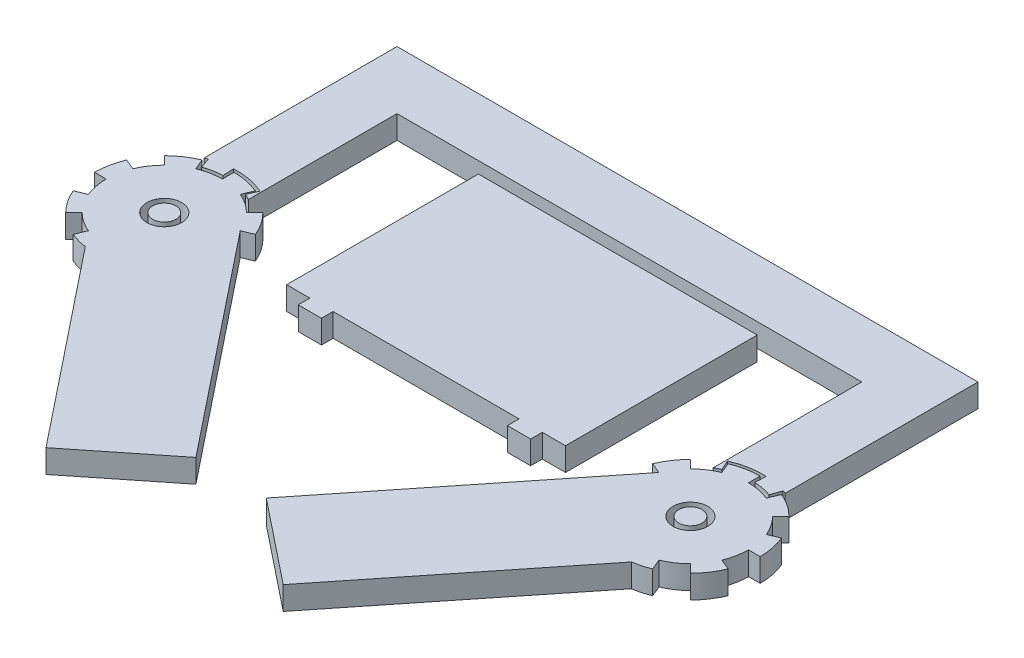
SolidWorks part; units mm, degrees
ref_plane "Front Plane" through (0, 0, 0) normal (0, 0, 1) x (1, 0, 0)
ref_plane "Top Plane" through (0, 0, 0) normal (0, 1, 0) x (1, 0, 0)
ref_plane "Right Plane" through (0, 0, 0) normal (1, 0, 0) x (0, 0, -1)
sketch "Sketch1" plane through (0, 0, 0) normal (0, 1, 0) x (1, 0, 0)
  line L0 (-20, 17.5) -> (20, 17.5)
  line L1 (-25, 22.5) -> (25, 22.5)
  line L2 (-25, 22.5) -> (-25, 5.8971)
  line L4 (25, 22.5) -> (25, 5.8971)
  line L5 (0, 0) -> (8.0037, 0)
  line L6 (0, 0) -> (-8.0037, 0)
  line L7 (20, 17.5) -> (20, 4.7044)
  line L9 (-20, 17.5) -> (-20, 4.7044)
  line L18 (0, 0) -> (0, -24.2528) construction
  line L19 (-23.5007, -5.8271) -> (-10.2099, -22.5)
  line L20 (-10.2099, -22.5) -> (-3.0312, -16.7775)
  line L21 (12, 0) -> (12, 16.5)
  line L22 (-12, 0) -> (-12, 16.5)
  line L23 (0, 17.5) -> (0, 16.5) construction
  line L24 (-12, 16.5) -> (12, 16.5)
  line L25 (-12, 0) -> (-10, 0) construction
  line L26 (-10, 0) -> (-10, -1)
  line L27 (-10, -1) -> (-8.0037, -1)
  line L28 (-8.0037, -1) -> (-8.0037, 0)
  line L29 (10, 0) -> (10, -1)
  line L30 (10, -1) -> (8.0037, -1)
  line L31 (8.0037, -1) -> (8.0037, 0)
  line L32 (-22.6382, 6.1106) -> (-22.6382, 5.1106)
  line L33 (-28.6382, 0.1106) -> (-27.6382, 0.1106)
  line L34 (-10, 0) -> (-12, 0)
  line L35 (10, 0) -> (12, 0)
  line L37 (-26.8808, -4.1321) -> (-26.1737, -3.4249)
  line L38 (-24.9343, -5.4327) -> (-24.5516, -4.5088)
  line L39 (-28.1814, -2.1855) -> (-27.2576, -1.8028)
  line L52 (-25, 22.5) -> (-25, -22.5) construction
  line L54 (-18.0188, 2.024) -> (-3.0312, -16.7775)
  line L55 (-20, 17.5) -> (-20, -17.5) construction
  line L58 (-20, -17.5) -> (20, -17.5) construction
  line L59 (-24.4164, 5.1054) -> (-24.7344, 5.9986)
  line L60 (-22.8806, 5.4069) -> (-22.9239, 6.3541)
  line L61 (-27.2576, 2.024) -> (-28.1814, 2.4067)
  line L62 (-20.5005, 4.9576) -> (-20.1161, 5.8291)
  line L63 (-26.1737, 3.6461) -> (-26.8808, 4.3532)
  line L64 (-24.5516, 4.73) -> (-24.9343, 5.6539)
  line L66 (-20.7247, 4.73) -> (-20.3421, 5.6539)
  line L67 (-19.1026, 3.6461) -> (-18.3955, 4.3532)
  line L68 (-18.0188, 2.024) -> (-17.0949, 2.4067)
  line L71 (10.2077, -22.5028) -> (3.0256, -16.7775)
  line L72 (23.5007, -5.8271) -> (10.2077, -22.5028)
  line L76 (25, 22.5) -> (25, 5.8971)
  line L77 (24.4164, 5.1054) -> (24.7344, 5.9986)
  line L78 (22.8806, 5.4069) -> (22.9239, 6.3541)
  line L79 (20.5005, 4.9576) -> (20.1161, 5.8291)
  line L80 (20, 17.5) -> (20, 4.7044)
  line L81 (18.0131, 2.024) -> (17.094, 2.4047)
  line L82 (19.1026, 3.6461) -> (18.3955, 4.3532)
  line L83 (20.7247, 4.73) -> (20.3421, 5.6539)
  line L84 (22.6382, 6.1106) -> (22.6382, 5.1106)
  line L85 (24.5516, 4.73) -> (24.9343, 5.6539)
  line L86 (26.1737, 3.6461) -> (26.8808, 4.3532)
  line L87 (27.2576, 2.024) -> (28.1814, 2.4067)
  line L88 (28.6382, 0.1106) -> (27.6382, 0.1106)
  line L89 (28.1814, -2.1855) -> (27.2576, -1.8028)
  line L90 (26.8808, -4.1321) -> (26.1737, -3.4249)
  line L91 (24.9343, -5.4327) -> (24.5516, -4.5088)
  line L98 (20, 17.5) -> (20, -17.5) construction
  line L100 (25, 22.5) -> (25, -22.5) construction
  line L101 (18.0131, 2.024) -> (3.0256, -16.7775)
  line L104 (-25, -22.5) -> (25, -22.5) construction
  arc A30 (-24.9343, 5.6539) -> (-26.8808, 4.3532) centre (-22.6382, 0.1106) ccw
  arc A31 (-26.1737, -3.4249) -> (-24.5516, -4.5088) centre (-22.6382, 0.1106) ccw
  arc A32 (-20.3421, 5.6539) -> (-22.6382, 6.1106) centre (-22.6382, 0.1106) ccw
  arc A33 (-17.0949, 2.4067) -> (-18.3955, 4.3532) centre (-22.6382, 0.1106) ccw
  arc A36 (-24.9343, -5.4327) -> (-23.5007, -5.8271) centre (-22.6382, 0.1106) ccw
  arc A37 (-28.1814, -2.1855) -> (-26.8808, -4.1321) centre (-22.6382, 0.1106) ccw
  arc A38 (-28.1814, 2.4067) -> (-28.6382, 0.1106) centre (-22.6382, 0.1106) ccw
  arc A39 (-25, 5.8971) -> (-24.7344, 5.9986) centre (-22.6382, 0.1106) cw
  arc A40 (-24.4164, 5.1054) -> (-22.8806, 5.4069) centre (-22.6382, 0.1106) cw
  arc A41 (-22.9239, 6.3541) -> (-20.1161, 5.8291) centre (-22.6382, 0.1106) cw
  arc A42 (-20, 4.7044) -> (-20.5005, 4.9576) centre (-22.6382, 0.1106) ccw
  arc A46 (-19.1026, 3.6461) -> (-20.7247, 4.73) centre (-22.6382, 0.1106) ccw
  arc A47 (-22.6382, 5.1106) -> (-24.5516, 4.73) centre (-22.6382, 0.1106) ccw
  arc A48 (-26.1737, 3.6461) -> (-27.2576, 2.024) centre (-22.6382, 0.1106) ccw
  arc A49 (-27.6382, 0.1106) -> (-27.2576, -1.8028) centre (-22.6382, 0.1106) ccw
  arc A50 (25, 5.8971) -> (24.7344, 5.9986) centre (22.6382, 0.1106) ccw
  arc A51 (24.4164, 5.1054) -> (22.8806, 5.4069) centre (22.6382, 0.1106) ccw
  arc A52 (22.9239, 6.3541) -> (20.1161, 5.8291) centre (22.6382, 0.1106) ccw
  arc A53 (20, 4.7044) -> (20.5005, 4.9576) centre (22.6382, 0.1106) cw
  arc A55 (17.094, 2.4047) -> (18.3955, 4.3532) centre (22.6382, 0.1106) cw
  arc A56 (19.1026, 3.6461) -> (20.7247, 4.73) centre (22.6382, 0.1106) cw
  arc A57 (20.3421, 5.6539) -> (22.6382, 6.1106) centre (22.6382, 0.1106) cw
  arc A58 (22.6382, 5.1106) -> (24.5516, 4.73) centre (22.6382, 0.1106) cw
  arc A59 (24.9343, 5.6539) -> (26.8808, 4.3532) centre (22.6382, 0.1106) cw
  arc A60 (26.1737, 3.6461) -> (27.2576, 2.024) centre (22.6382, 0.1106) cw
  arc A61 (28.1814, 2.4067) -> (28.6382, 0.1106) centre (22.6382, 0.1106) cw
  arc A62 (27.6382, 0.1106) -> (27.2576, -1.8028) centre (22.6382, 0.1106) cw
  arc A63 (28.1814, -2.1855) -> (26.8808, -4.1321) centre (22.6382, 0.1106) cw
  arc A64 (26.1737, -3.4249) -> (24.5516, -4.5088) centre (22.6382, 0.1106) cw
  arc A65 (24.9343, -5.4327) -> (23.5007, -5.8271) centre (22.6382, 0.1106) cw
  circle A70 centre (-22.6382, 0.1106) radius 1.004
  circle A71 centre (-22.6382, 0.1106) radius 1.498
  circle A72 centre (22.6382, 0.1106) radius 1.498
  circle A73 centre (22.6382, 0.1106) radius 1.004
  point P0 (0, 0)
  point P20 (0, 0)
  point P28 (0, 16.5)
  point P30 (-22.6382, 0.1106)
  point P34 (-22.6382, 0.1106)
  point P91 (-22.6382, 0.1106)
  point P98 (-22.6382, 0.1106)
  point P100 (-22.6382, 0.1106)
  dimension "D4" = 1
  dimension "D5" = 2
  dimension "D1" = 12
  dimension "D2" = 90
  dimension "D6" = 1
  dimension "D3" = 5
extrude "Boss-Extrude2" add sketch "Sketch1" along normal blind 2 contours A65 L91 A64 L90 A63 L89 A62 L88 A61 L87 A60 L86 A59 L85 A58 L84 A57 L83 A56 L82 A55 L81 L101 L71 L72 A72 | L33 A49 L39 A37 L37 A31 L38 A36 L19 L20 L54 L68 A33 L67 A46 L66 A32 L32 A47 L64 A30 L63 A48 L61 A38 A71 | L29 L35 L21 L24 L22 L34 L26 L27 L28 L6 L5 L31 L30 | L7 A53 L79 A52 L78 A51 L77 A50 L4 L1 L2 A39 L59 A40 L60 A41 L62 A42 L9 L0
sketch "Sketch2" plane through (0, 0, 0) normal (0, 1, 0) x (1, 0, 0)
  circle A0 centre (22.6382, 0.1106) radius 1
  circle A1 centre (-22.6382, 0.1106) radius 1
  dimension "D1" = 2
extrude "Boss-Extrude4" add sketch "Sketch2" along normal blind 2 separate body
